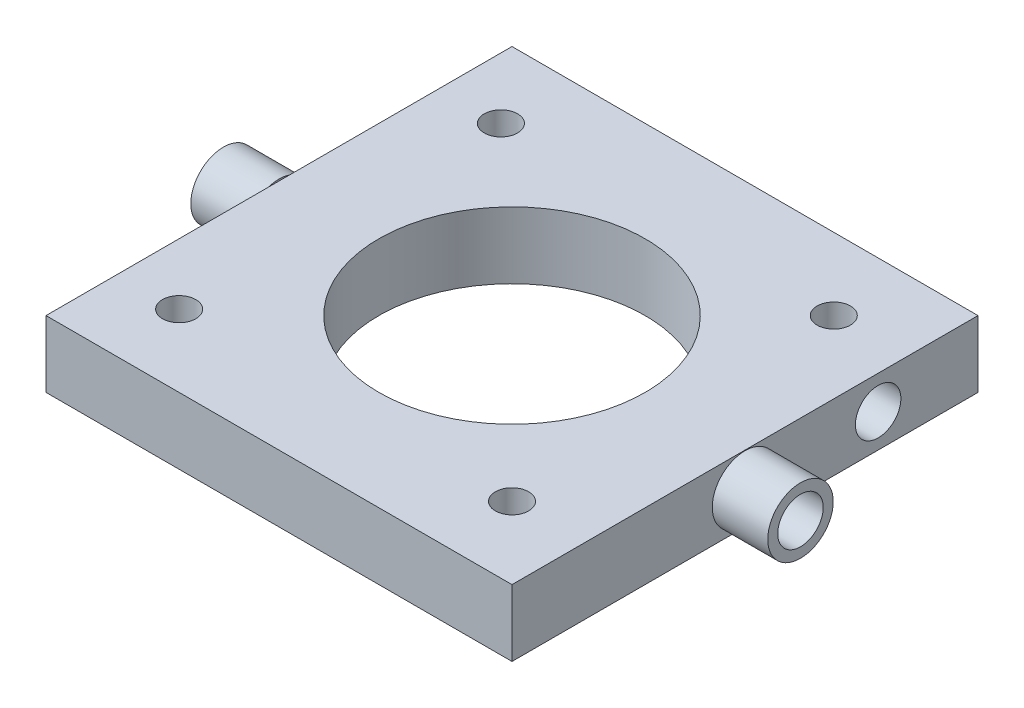
SolidWorks part; units mm, degrees
ref_plane "Alzado" through (0, 0, 0) normal (0, 0, 1) x (1, 0, 0)
ref_plane "Planta" through (0, 0, 0) normal (0, 1, 0) x (1, 0, 0)
ref_plane "Vista lateral" through (0, 0, 0) normal (1, 0, 0) x (0, 0, -1)
sketch "Croquis1" plane through (0, 0, 0) normal (0, 1, 0) x (1, 0, 0)
  line L1 (-21, -21) -> (21, -21)
  line L2 (-21, -21) -> (-21, 21)
  line L3 (-21, 21) -> (21, 21)
  line L4 (21, -21) -> (21, 21)
  line L5 (-21, -21) -> (21, 21) construction
  line L6 (-21, 21) -> (21, -21) construction
  point P0 (0, 0)
  dimension "D1" = 42
  dimension "D2" = 42
extrude "Saliente-Extruir1" add sketch "Croquis1" along normal blind 6
sketch "Croquis2" plane through (0, 6, 0) normal (0, 1, 0) x (1, 0, 0)
  line L0 (-21, -21) -> (21, -21) construction
  line L1 (-21, 21) -> (-21, -21) construction
  line L2 (21, 21) -> (-21, 21) construction
  circle A0 centre (-15.5, -14.5) radius 1.5
  circle A1 centre (14.5, -14.5) radius 1.5
  circle A2 centre (14.5, 14.5) radius 1.5
  circle A3 centre (-15.5, 14.5) radius 1.5
  circle A4 centre (0, 0) radius 12
  dimension "D1" = 6.5
  dimension "D2" = 5.5
  dimension "D6" = 5.5
  dimension "D7" = 24
  dimension "D8" = 3
  dimension "D5" = 6.5
  dimension "D3" = 2
  dimension "D4" = 2
extrude "Cortar-Extruir2" cut sketch "Croquis2" against normal blind 6
sketch "Croquis4" plane through (21, 0, 0) normal (1, 0, 0) x (0, 0, -1)
  line L0 (21, 3) -> (12, 3) construction
  line L1 (21, 6) -> (21, 0) construction
  line L2 (12, 3) -> (0, 3) construction
  circle A0 centre (12, 3) radius 2.05
  circle A1 centre (0, 3) radius 2.05
  dimension "D3" = 4.1
  dimension "D4" = 4.1
  dimension "D1" = 9
  dimension "D2" = 12
extrude "Cortar-Extruir3" cut sketch "Croquis4" against normal blind 3
sketch "Croquis5" plane through (-21, 0, 0) normal (-1, 0, 0) x (0, 0, 1)
  line L0 (-21, 6) -> (-21, 0) construction
  circle A0 centre (-12, 3.2069) radius 2.05
  circle A1 centre (0, 3.2069) radius 2.05
  dimension "D1" = 4.1
  dimension "D2" = 12
  dimension "D3" = 9
extrude "Cortar-Extruir4" cut sketch "Croquis5" against normal blind 3
sketch "Croquis6" plane through (21, 0, 0) normal (1, 0, 0) x (0, 0, -1)
  circle A0 centre (0, 3) radius 2.95
  circle A2 centre (0, 3) radius 2.05
  dimension "D1" = 5.9
extrude "Saliente-Extruir2" add sketch "Croquis6" along normal blind 5
sketch "Croquis7" plane through (-21, 0, 0) normal (-1, 0, 0) x (0, 0, 1)
  circle A1 centre (0, 3.2069) radius 2.95
  circle A4 centre (0, 3.2069) radius 2.05
extrude "Saliente-Extruir3" add sketch "Croquis7" along normal blind 5
